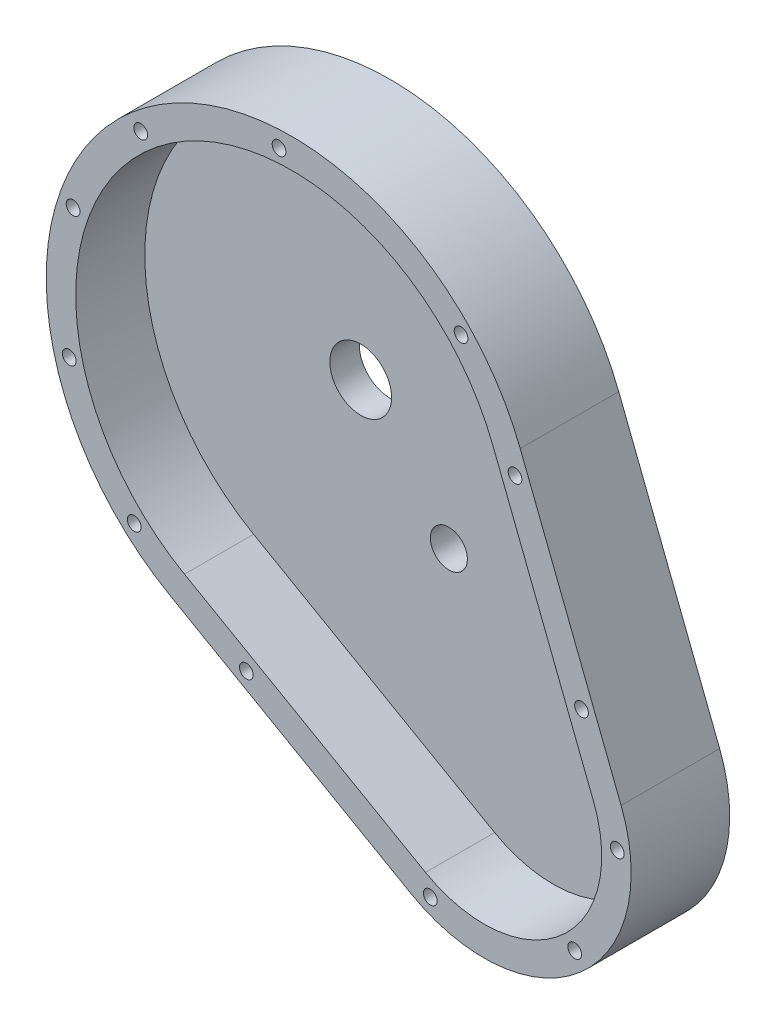
SolidWorks part; units mm, degrees
ref_plane "Front Plane" through (0, 0, 0) normal (0, 0, 1) x (1, 0, 0)
ref_plane "Top Plane" through (0, 0, 0) normal (0, 1, 0) x (1, 0, 0)
ref_plane "Right Plane" through (0, 0, 0) normal (1, 0, 0) x (0, 0, -1)
sketch "Sketch1" plane through (0, 0, 0) normal (0, 0, 1) x (1, 0, 0)
  line L0 (0, 0) -> (31.1871, -17.8237)
  line L1 (58.3872, 5.6385) -> (45.3334, 39.1037)
  arc A0 (31.1871, -17.8237) -> (58.3872, 5.6385) centre (40.6396, -1.2843) ccw
  arc A1 (45.3334, 39.1037) -> (0, 0) centre (15.7541, 27.5658) ccw
  dimension "D1" = 19.05
  dimension "D2" = 31.75
  dimension "D3" = 88.9
extrude "Boss-Extrude1" add sketch "Sketch1" along normal blind 12.7508
shell "Shell2" thickness 3.81
hole_wizard "#50 (0.07) Diameter Hole3" positions "Sketch13" profile "Sketch14" hole size "#50" standard "ANSI Inch" end condition through all
sketch "Sketch13" plane through (0, 0, 12.7508) normal (0, 0, 1) x (1, 0, 0)
  point P0 (-3.7702, 50.0984)
  point P2 (14.1273, 57.1787)
  point P4 (37.6792, 48.0333)
  point P8 (57.8876, 0.3886)
  point P10 (52.3807, -13.6245)
  point P12 (33.6965, -16.968)
  point P14 (9.8988, -3.5449)
  point P16 (-4.606, 5.7481)
  point P18 (-13.0139, 20.1545)
  point P20 (-12.5222, 37.167)
  point P28 (44.6612, 35.7411)
  point P30 (53.2657, 13.8609)
sketch "Sketch14" plane through (-3.7702, 50.0984, 12.7508) normal (1, 0, 0) x (0, -1, 0)
  line L0 (0, 0) -> (0, 12.7508)
  line L1 (0, 12.7508) -> (0.889, 12.7508)
  line L2 (0.889, 12.7508) -> (0.889, 0)
  line L5 (0.889, 0) -> (0, 0)
  line L11 (0, -6.35) -> (0, 107.95) construction
  dimension "Thru Hole Dia." = 1.778
  dimension "Thru Hole Depth" = 12.7508
sketch "Sketch15" plane through (0, 0, 3.81) normal (0, 0, 1) x (1, 0, 0)
  circle A0 centre (15.7541, 27.5658) radius 3.9942
  dimension "D1" = 7.9883
extrude "Cut-Extrude2" cut sketch "Sketch15" against normal through all
sketch "Sketch16" plane through (0, 0, 3.81) normal (0, 0, 1) x (1, 0, 0)
  line L0 (15.7541, 27.5658) -> (40.6396, -1.2843) construction
  circle A1 centre (27.1599, 14.3428) radius 2.3939
  dimension "D1" = 4.7879
  dimension "D2" = 17.4625
extrude "Cut-Extrude3" cut sketch "Sketch16" against normal through all
equation "\"gear1\"= 1.063in"
equation "\"gear2\"= .438in"
equation "\"gearh\"= .438in"
equation "\"T\"= \"gearh\" + .064in"
equation "\"D1@Boss-Extrude1\"=\"T\""
equation "\"bearing1\"= .3145in"
equation "\"bearing2\"= .1885in"
equation "\"D1@Sketch15\"= \"bearing1\""
equation "\"pitch1\"= 1in"
equation "\"pitch2\"= .375in"
equation "\"D1@Sketch16\"=\"bearing2\""
equation "\"D2@Sketch16\"=\"Lbetwen\""
equation "\"Lbetwen\" = ( \"pitch1\" / 2 ) + ( \"pitch2\" / 2 )"
